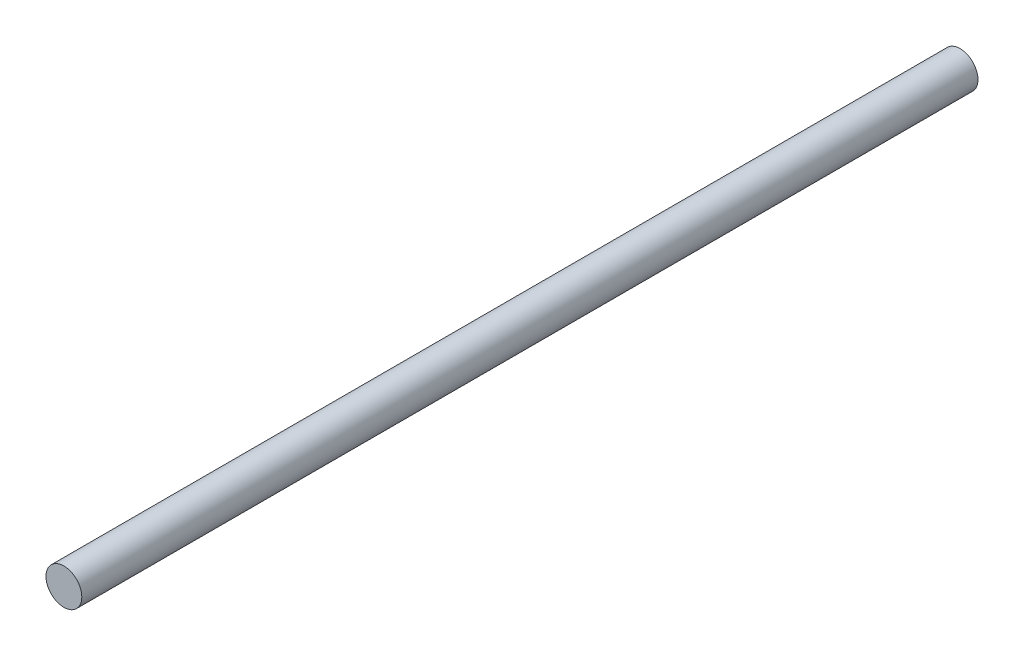
SolidWorks part; units mm, degrees
ref_plane "前视基准面" through (0, 0, 0) normal (0, 0, 1) x (1, 0, 0)
ref_plane "上视基准面" through (0, 0, 0) normal (0, 1, 0) x (1, 0, 0)
ref_plane "右视基准面" through (0, 0, 0) normal (1, 0, 0) x (0, 0, -1)
other "Configuration Table"
sketch "草图1" plane through (0, 0, 0) normal (0, 0, 1) x (1, 0, 0)
  circle A0 centre (0, 0) radius 4
  dimension "D1" = 8
extrude "凸台-拉伸1" add sketch "草图1" along normal blind 200
